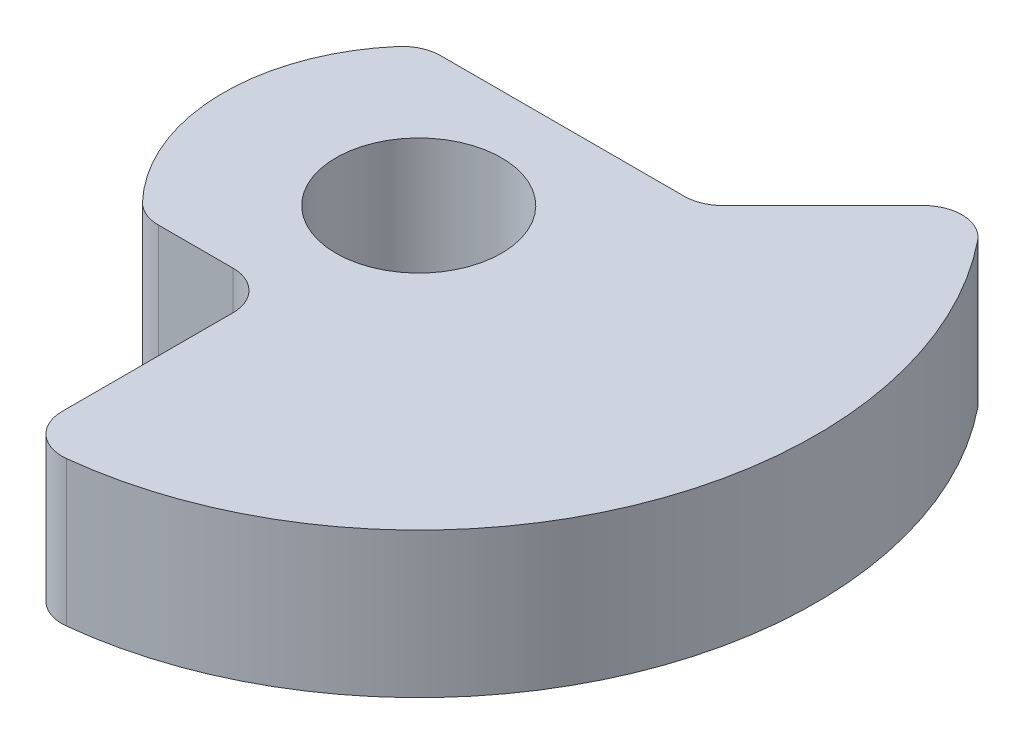
SolidWorks part; units mm, degrees
ref_plane "Front Plane" through (0, 0, 0) normal (0, 0, 1) x (1, 0, 0)
ref_plane "Top Plane" through (0, 0, 0) normal (0, 1, 0) x (1, 0, 0)
ref_plane "Right Plane" through (0, 0, 0) normal (1, 0, 0) x (0, 0, -1)
sketch "Sketch11" plane through (0, 0, 0) normal (0, 1, 0) x (1, 0, 0)
  line L1 (59.1891, -16.8566) -> (41.5057, -16.8566)
  line L2 (41.5057, -35.751) -> (49.948, -35.751)
  line L4 (49.948, -35.751) -> (49.948, -52.1953)
  line L6 (76.0457, -26.0977) -> (76.0857, -26.0977)
  line L7 (59.1891, -16.8566) -> (68.4302, -7.6155)
  arc A0 (49.948, -52.1953) -> (68.4019, -7.6438) centre (49.948, -26.0977) ccw
  circle A1 centre (49.948, -26.0977) radius 5.4343
  arc A2 (41.5057, -16.8566) -> (41.0385, -16.8738) centre (41.5057, -23.2066) ccw
  arc A4 (41.0385, -16.8738) -> (41.5057, -35.751) centre (49.948, -26.0977) ccw
  dimension "D1" = 6.35
extrude "Extrude5" add sketch "Sketch11" against normal blind 9.525
ref_plane "Plane4" through (0, 0, 26.0977) normal (0, 0, 1) x (1, 0, 0)
fillet "Fillet2" radius 2.54 2 edges at (59.1891, -4.7625, 16.8566) (49.948, -4.7625, 35.751)
fillet "Fillet1" radius 2.54 2 edges at (68.4019, -4.7625, 7.6438) (49.948, -4.7625, 52.1953)
fillet "Fillet3" radius 2.54 2 edges at (41.0385, -4.7625, 16.8738) (41.5057, -4.7625, 35.751)
sketch "Sketch12" plane through (0, 0, 0) normal (0, 1, 0) x (1, 0, 0)
  line L0 (65.2989, -26.1269) -> (71.9916, -26.1269)
sketch "Sketch13" plane through (0, 0, 26.0977) normal (0, 0, 1) x (1, 0, 0)
  line L0 (71.9916, 0) -> (71.9916, -1.5632)
  line L1 (71.2296, -2.3252) -> (69.8961, -2.3252)
  line L2 (69.1341, -3.0872) -> (69.1341, -3.81)
  line L3 (68.3721, -4.572) -> (65.1336, -4.572)
  line L4 (64.3716, 0) -> (64.3716, -3.81)
  line L5 (64.3716, 0) -> (71.9916, 0)
  line L6 (49.948, 0) -> (49.948, 16.1529) construction
  arc A0 (71.9916, -1.5632) -> (71.2296, -2.3252) centre (71.2296, -1.5632) cw
  arc A1 (69.1341, -3.81) -> (68.3721, -4.572) centre (68.3721, -3.81) cw
  arc A2 (64.3716, -3.81) -> (65.1336, -4.572) centre (65.1336, -3.81) ccw
  arc A3 (69.8961, -2.3252) -> (69.1341, -3.0872) centre (69.8961, -3.0872) ccw
  dimension "D1" = 0.762
  dimension "D2" = 7.62
  dimension "D3" = 4.7625
  dimension "D4" = 4.572
  dimension "D5" = 2.3252
